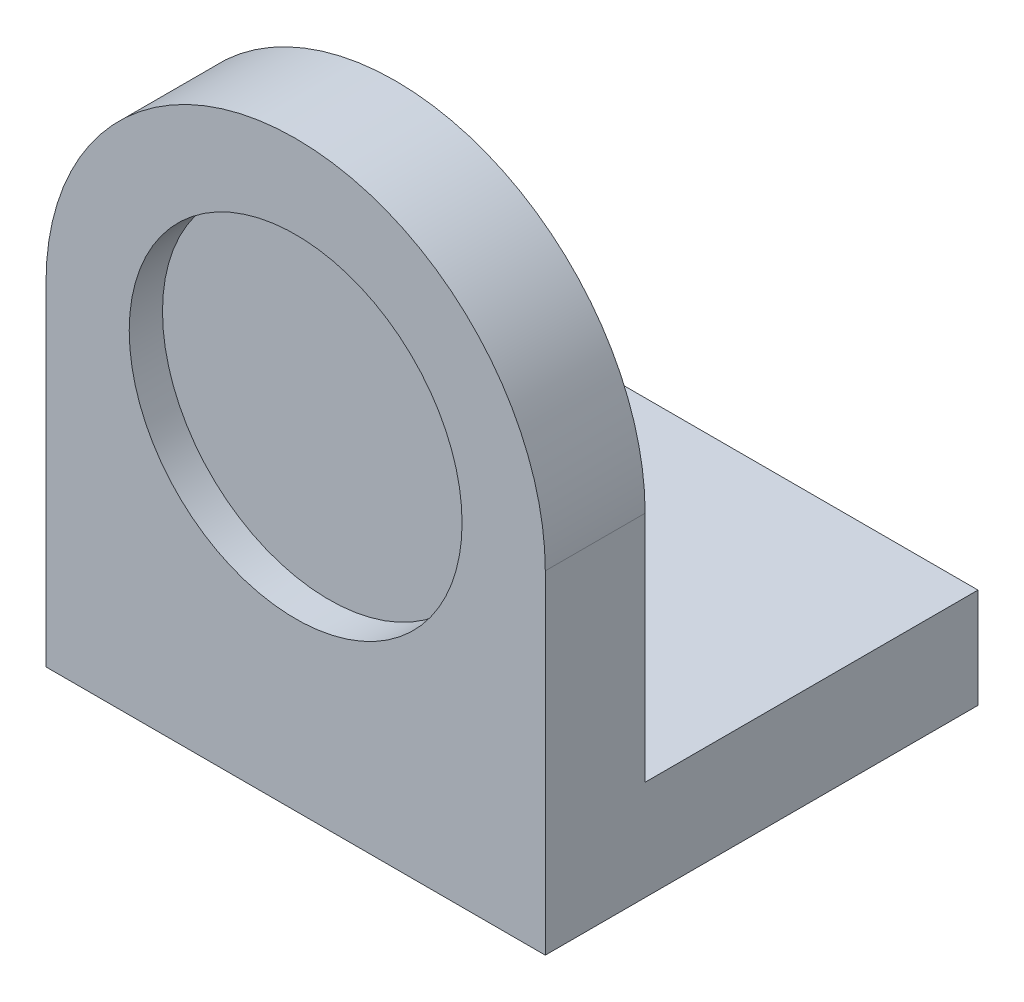
SolidWorks part; units mm, degrees
ref_plane "Front Plane" through (0, 0, 0) normal (0, 0, 1) x (1, 0, 0)
ref_plane "Top Plane" through (0, 0, 0) normal (0, 1, 0) x (1, 0, 0)
ref_plane "Right Plane" through (0, 0, 0) normal (1, 0, 0) x (0, 0, -1)
sketch "Sketch6" plane through (0, 0, 0) normal (0, 0, 1) x (1, 0, 0)
  line L0 (-7.5, 0) -> (-7.5, -10)
  line L1 (-7.5, -10) -> (7.5, -10)
  line L2 (7.5, -10) -> (7.5, 0)
  circle A0 centre (0, 0) radius 5
  arc A1 (7.5, 0) -> (-7.5, 0) centre (0, 0) ccw
  dimension "D1" = 10
  dimension "D2" = 15
  dimension "D3" = 10
extrude "Boss-Extrude5" add sketch "Sketch6" along normal blind 3
sketch "Sketch7" plane through (0, 0, 0) normal (0, 0, -1) x (-1, 0, 0)
  circle A0 centre (0, 0) radius 5
extrude "Boss-Extrude6" add sketch "Sketch7" against normal blind 2
sketch "Sketch8" plane through (0, 0, 0) normal (0, 0, -1) x (-1, 0, 0)
  line L0 (7.5, 0) -> (7.5, -10) construction
  line L1 (-7.5, -10) -> (7.5, -10)
  line L2 (-7.5, -10) -> (-7.5, -7)
  line L3 (-7.5, -7) -> (7.5, -7)
  line L4 (7.5, -10) -> (7.5, -7)
  dimension "D1" = 3
extrude "Boss-Extrude7" add sketch "Sketch8" along normal blind 10
